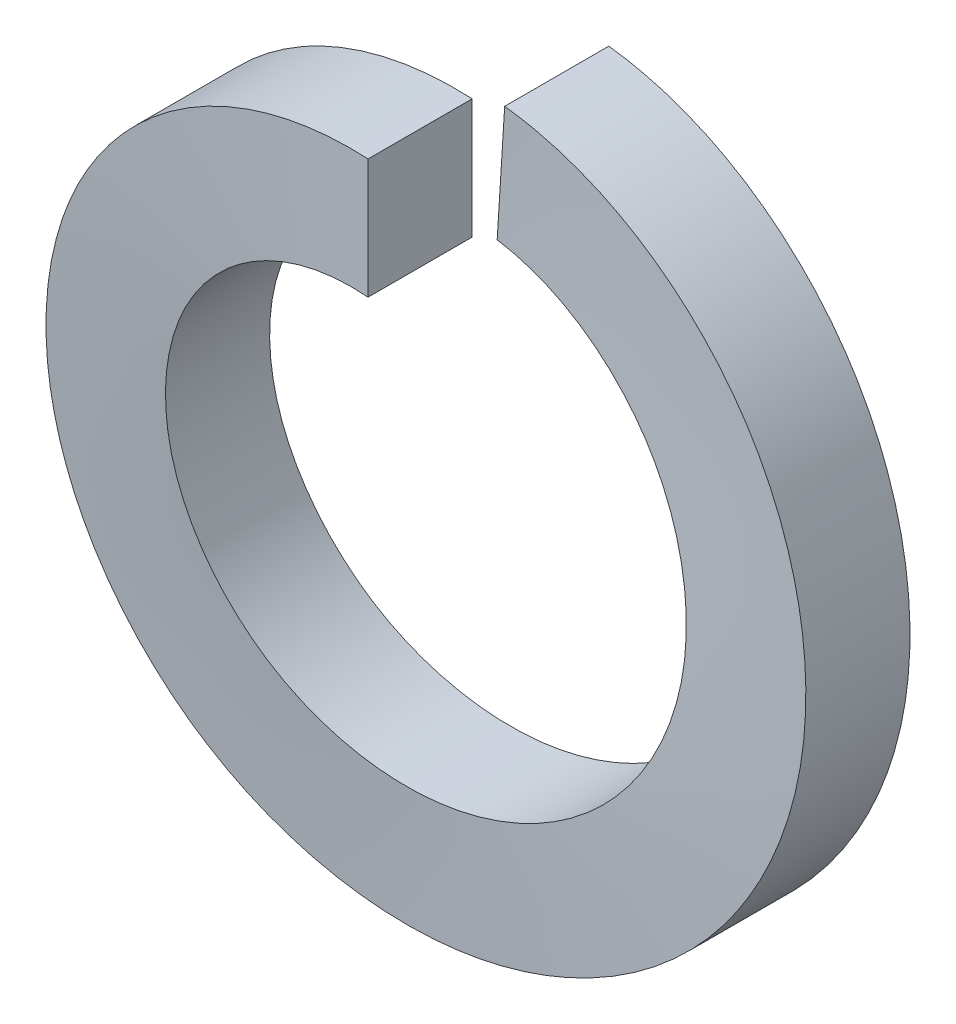
SolidWorks part; units mm, degrees
material "AISI 304"
ref_plane "Front Plane" through (0, 0, 0) normal (0, 0, 1) x (1, 0, 0)
ref_plane "Top Plane" through (0, 0, 0) normal (0, 1, 0) x (1, 0, 0)
ref_plane "Right Plane" through (0, 0, 0) normal (1, 0, 0) x (0, 0, -1)
sketch "Sketch1" plane through (0, 0, 0) normal (0, 0, 1) x (1, 0, 0)
  line L0 (0, 2.5654) -> (0, 1.6891) construction
  circle A0 centre (0, 0) radius 2.5654
  circle A1 centre (0, 0) radius 1.6891 construction
  dimension "ID" = 3.3782
  dimension "OD" = 5.1308
curve "Helix/Spiral1" pitch 0.8467 height 0.8382 turns 0.99 parameters "HT"=0.8382
sketch "Sketch2" plane through (0, 0, 0) normal (1, 0, 0) x (0, 0, -1)
  line L1 (0, 2.5654) -> (-0.762, 2.5654)
  line L2 (0, 2.5654) -> (0, 1.6891)
  line L3 (0, 1.6891) -> (-0.762, 1.6891)
  line L4 (-0.762, 2.5654) -> (-0.762, 1.6891)
  dimension "THK" = 0.762
sweep "Sweep1" add profiles "Sketch2" path "Helix/Spiral1"
equation "\"HT@Helix/Spiral1\" = \"THK@Sketch2\"*1.1"
